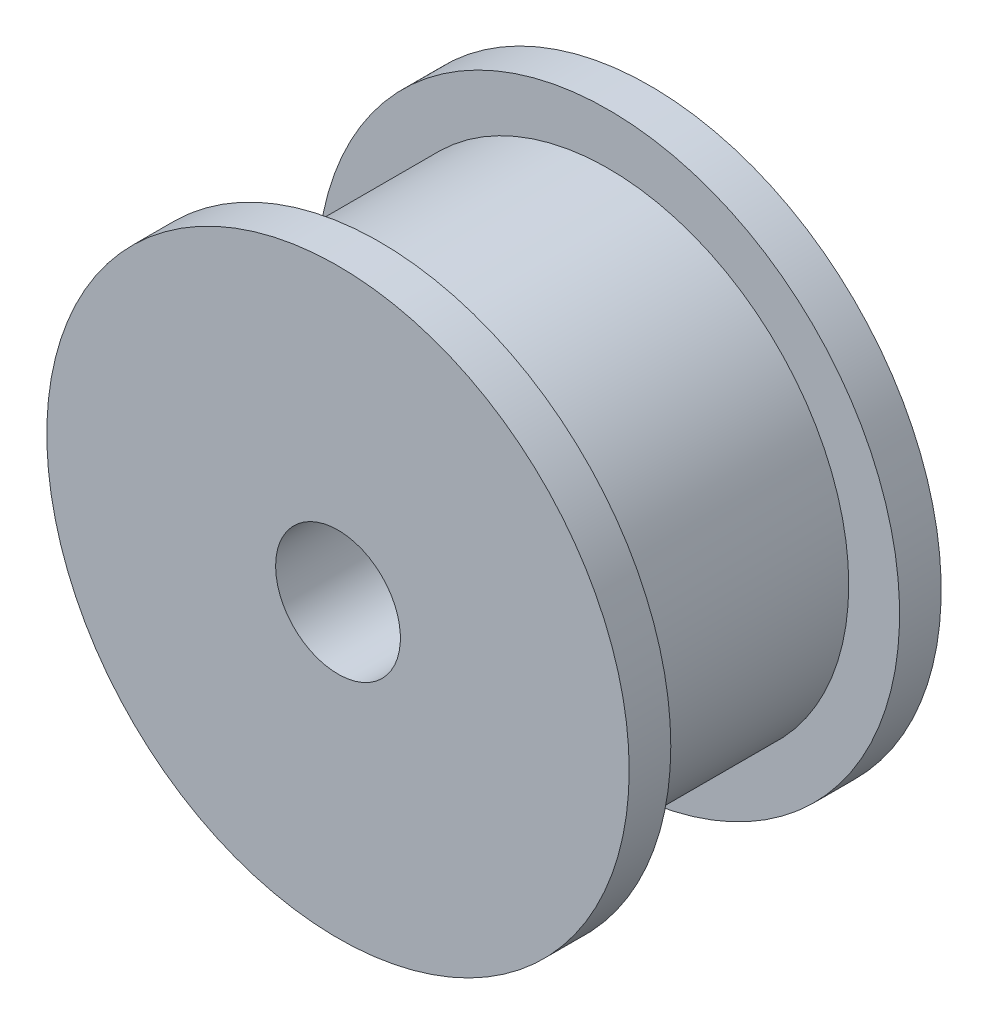
SolidWorks part; units mm, degrees
ref_plane "前视基准面" through (0, 0, 0) normal (0, 0, 1) x (1, 0, 0)
ref_plane "上视基准面" through (0, 0, 0) normal (0, 1, 0) x (1, 0, 0)
ref_plane "右视基准面" through (0, 0, 0) normal (1, 0, 0) x (0, 0, -1)
other "Configuration Table"
sketch "草图1" plane through (0, 0, 0) normal (0, 0, 1) x (1, 0, 0)
  circle A0 centre (0, 0) radius 11.555
  dimension "D1" = 23.11
extrude "凸台-拉伸1" add sketch "草图1" along normal blind 11
sketch "草图2" plane through (0, 0, 11) normal (0, 0, 1) x (1, 0, 0)
  circle A0 centre (0, 0) radius 14
  dimension "D1" = 28
extrude "凸台-拉伸2" add sketch "草图2" along normal blind 2
sketch "草图3" plane through (0, 0, 0) normal (0, 0, -1) x (-1, 0, 0)
  circle A1 centre (0, 0) radius 14 construction
  circle A2 centre (0, 0) radius 14
extrude "凸台-拉伸3" add sketch "草图3" along normal blind 2
sketch "草图4" plane through (0, 0, -2) normal (0, 0, -1) x (-1, 0, 0)
  circle A0 centre (0, 0) radius 3
  dimension "D1" = 6
extrude "切除-拉伸1" cut sketch "草图4" against normal through all
